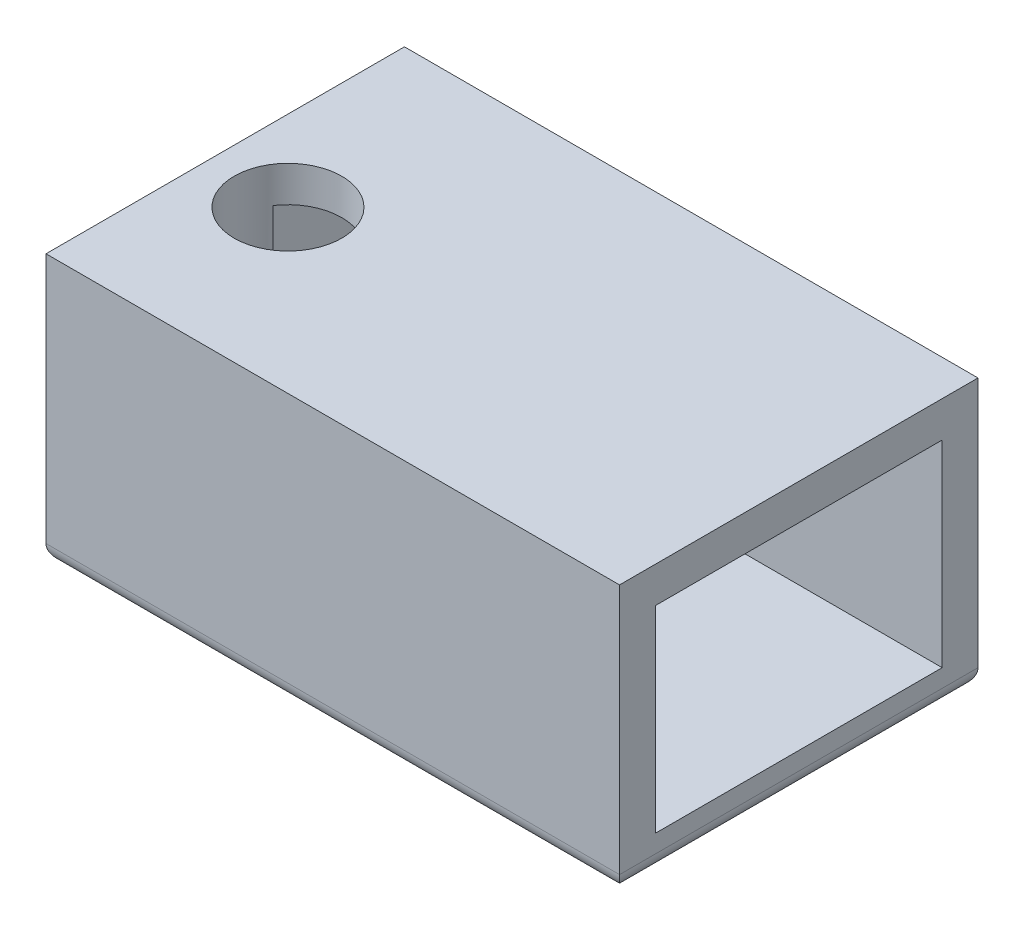
SolidWorks part; units mm, degrees
ref_plane "Front Plane" through (0, 0, 0) normal (0, 0, 1) x (1, 0, 0)
ref_plane "Top Plane" through (0, 0, 0) normal (0, 1, 0) x (1, 0, 0)
ref_plane "Right Plane" through (0, 0, 0) normal (1, 0, 0) x (0, 0, -1)
sketch "Sketch1" plane through (0, 0, 0) normal (0, 1, 0) x (1, 0, 0)
  line L1 (-15, -8) -> (15, -8)
  line L2 (-15, -8) -> (-15, 8)
  line L3 (-15, 8) -> (15, 8)
  line L4 (15, -8) -> (15, 8)
  line L5 (-15, -8) -> (15, 8) construction
  line L6 (-15, 8) -> (15, -8) construction
  point P0 (0, 0)
  dimension "D1" = 30
  dimension "D2" = 16
extrude "Boss-Extrude1" add sketch "Sketch1" along normal blind 11
shell "Shell1" thickness 2
sketch "Sketch4" plane through (0, 13, 0) normal (0, 1, 0) x (1, 0, 0)
  line L1 (-15, 8) -> (-15, -8) construction
  line L2 (-17, 0) -> (15, 0) construction
  line L3 (-17, 10) -> (-17, -10) construction
  line L4 (15, -10) -> (15, 10) construction
  circle A0 centre (-12.5, -1) radius 3
  dimension "D1" = 6
  dimension "D2" = 2.5
  dimension "D3" = 1
extrude "Cut-Extrude3" cut sketch "Sketch4" against normal up to surface (13 mm away) up to face at (0, 0, 0)
fillet "Fillet1" radius 1 4 edges at (-17, -2, 0) (-1, -2, -10) (15, -2, 0) (-1, -2, 10)
